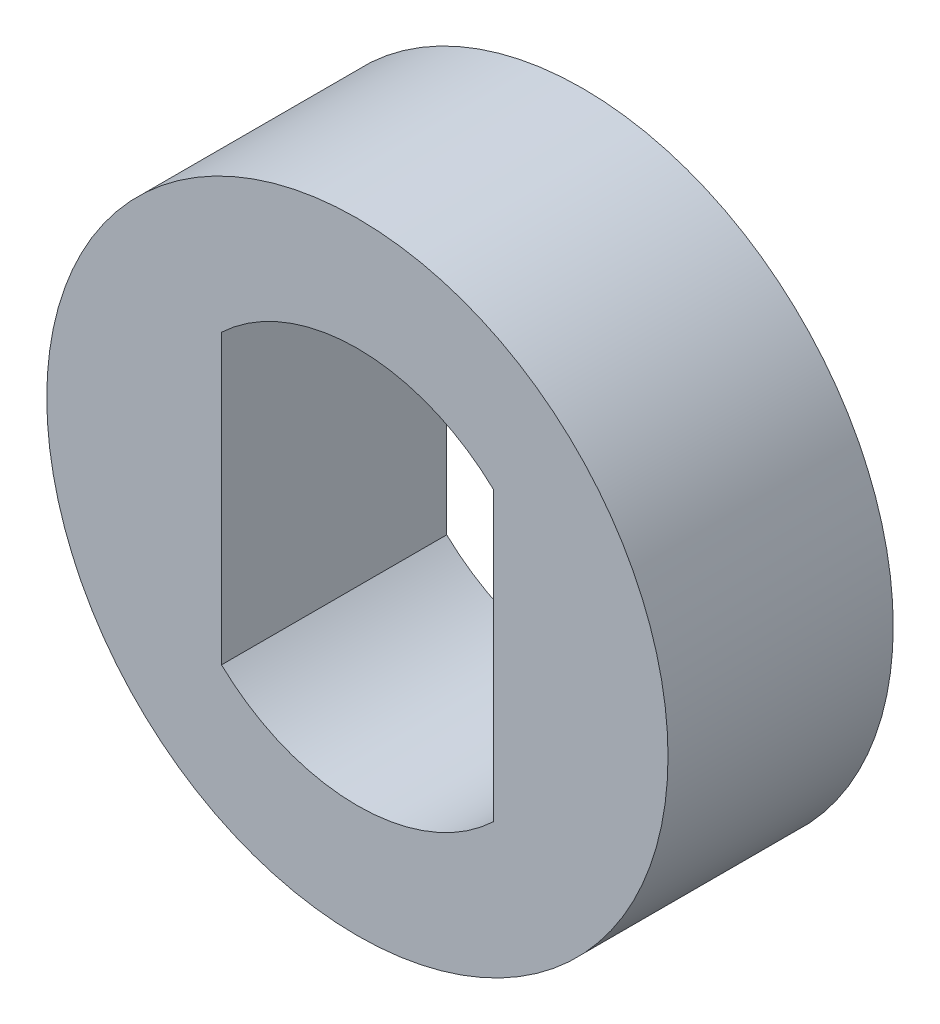
SolidWorks part; units mm, degrees
ref_plane "Front Plane" through (0, 0, 0) normal (0, 0, 1) x (1, 0, 0)
ref_plane "Top Plane" through (0, 0, 0) normal (0, 1, 0) x (1, 0, 0)
ref_plane "Right Plane" through (0, 0, 0) normal (1, 0, 0) x (0, 0, -1)
sketch "Sketch1" plane through (0, 0, 0) normal (0, 0, 1) x (1, 0, 0)
  line L2 (1.75, -1.8547) -> (1.75, 1.8547)
  line L4 (-1.75, -1.8547) -> (-1.75, 1.8547)
  line L5 (1.75, -1.8547) -> (-1.75, 1.8547) construction
  line L6 (1.75, 1.8547) -> (-1.75, -1.8547) construction
  arc A0 (-1.75, -1.8547) -> (1.75, -1.8547) centre (0, 0) ccw
  circle A1 centre (0, 0) radius 4
  arc A2 (1.75, 1.8547) -> (-1.75, 1.8547) centre (0, 0) ccw
  dimension "D1" = 3.5
  dimension "D2" = 2.55
  dimension "D3" = 8
extrude "Boss-Extrude1" add sketch "Sketch1" along normal mid plane 2.9
